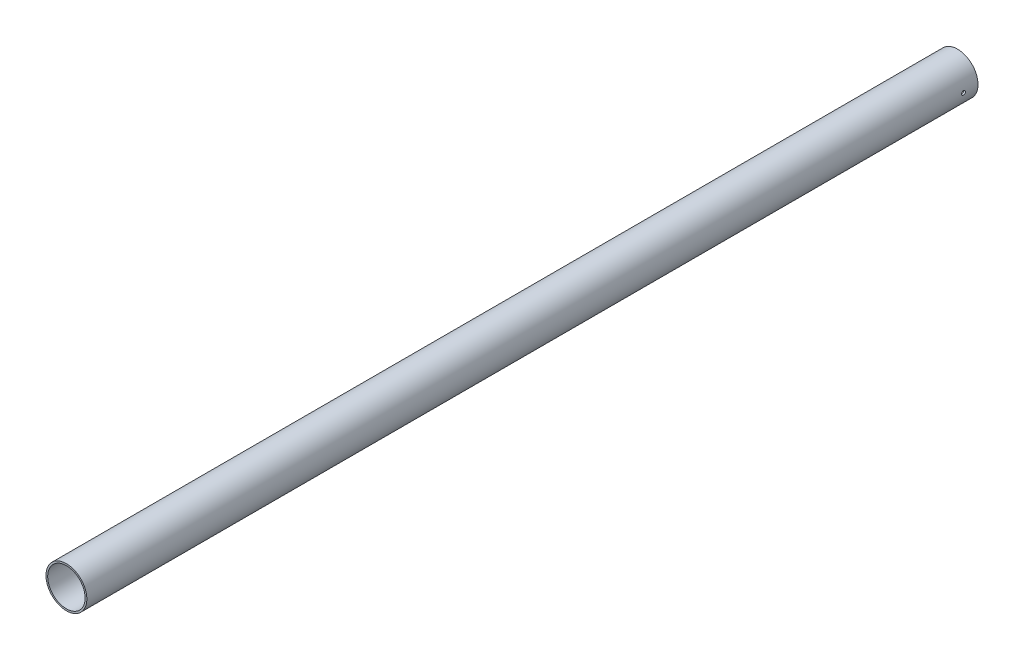
SolidWorks part; units mm, degrees
material "PC High Viscosity"
ref_plane "Front Plane" through (0, 0, 0) normal (0, 0, 1) x (1, 0, 0)
ref_plane "Top Plane" through (0, 0, 0) normal (0, 1, 0) x (1, 0, 0)
ref_plane "Right Plane" through (0, 0, 0) normal (1, 0, 0) x (0, 0, -1)
sketch "Sketch1" plane through (0, 0, 0) normal (0, 0, 1) x (1, 0, 0)
  circle A0 centre (0, 0) radius 12.7
  circle A1 centre (0, 0) radius 11.6205
  dimension "D1" = 25.4
  dimension "D2" = 23.241
extrude "Boss-Extrude1" add sketch "Sketch1" along normal blind 553.63
hole_wizard "M2 Clearance Hole1" positions "Sketch2" profile "Sketch3" hole size "M2" standard "ANSI Metric"
sketch "Sketch2" plane through (0, 0, 0) normal (1, 0, 0) x (0, 0, -1)
  line L1 (0, -12.7) -> (0, 12.7) construction
  point P0 (-9, 0)
  dimension "D1" = 9
sketch "Sketch3" plane through (0, 0, 9) normal (0, 1, 0) x (0, 0, 1)
  line L0 (0, 0) -> (0, 12.7)
  line L1 (0, 12.7) -> (1.2, 12.7)
  line L2 (1.2, 12.7) -> (1.2, 0)
  line L5 (1.2, 0) -> (0, 0)
  line L11 (0, -6.35) -> (0, 107.95) construction
  dimension "Thru Hole Dia." = 2.4
  dimension "Thru Hole Depth" = 12.7
mirror "Mirror1" about plane through (0, 0, 0) normal (1, 0, 0) of "M2 Clearance Hole1"
